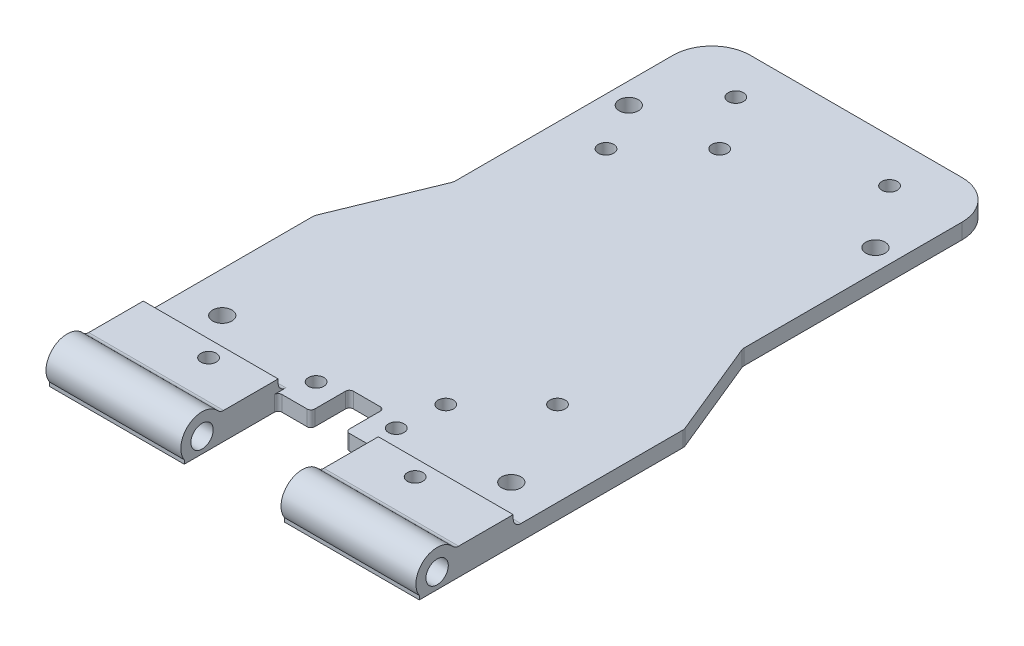
SolidWorks part; units mm, degrees
ref_plane "Front Plane" through (0, 0, 0) normal (0, 0, 1) x (1, 0, 0)
ref_plane "Top Plane" through (0, 0, 0) normal (0, 1, 0) x (1, 0, 0)
ref_plane "Right Plane" through (0, 0, 0) normal (1, 0, 0) x (0, 0, -1)
sketch "Sketch1" plane through (0, 0, 0) normal (0, 1, 0) x (1, 0, 0)
  line L0 (0, 0) -> (0, 23)
  line L1 (0, 23) -> (8.5, 23)
  line L2 (26, 23) -> (26, 0)
  line L3 (26, 0) -> (61, 0)
  line L4 (61, 0) -> (61, 28.8014)
  line L5 (61, 28.8014) -> (50.5, 57.5081) construction
  line L6 (50.5, 93.0296) -> (50.5, 160)
  line L7 (50.5, 160) -> (-24.5, 160)
  line L8 (-24.5, 160) -> (-24.5, 93.0296)
  line L9 (-24.5, 57.5081) -> (-35, 28.8014) construction
  line L10 (-35, 28.8014) -> (-35, 0)
  line L11 (-35, 0) -> (0, 0)
  line L12 (17.5, 23) -> (26, 23)
  line L14 (8.5, 23) -> (8.5, 33)
  line L15 (8.5, 33) -> (17.5, 33)
  line L16 (17.5, 23) -> (17.5, 33)
  line L17 (-35, 28.8014) -> (-35, 67.4062)
  line L24 (-35, 67.4062) -> (-24.5, 93.0296)
  line L26 (61, 67.4062) -> (50.5, 93.0296)
  line L27 (61, 28.8014) -> (61, 67.4062)
  point P16 (13, 33)
  point P22 (13, 160)
  point P24 (12, 23)
  dimension "D1" = 26
  dimension "D2" = 23
  dimension "D3" = 75
  dimension "D4" = 96
  dimension "D5" = 38.6048
  dimension "D6" = 28.8014
  dimension "D7" = 9
  dimension "D8" = 10
  dimension "D11" = 160
  dimension "D12" = 25.6234
extrude "Boss-Extrude1" add sketch "Sketch1" along normal blind 3
sketch "Sketch5" plane through (0, 3, 0) normal (0, 1, 0) x (1, 0, 0)
  line L0 (26, 23) -> (26, 0) construction
  line L1 (0, 23) -> (-35, 23)
  line L2 (0, 23) -> (0, 0)
  line L3 (0, 0) -> (-35, 0)
  line L4 (-35, 23) -> (-35, 0)
  line L5 (26, 23) -> (61, 23)
  line L6 (26, 23) -> (26, 0)
  line L7 (26, 0) -> (61, 0)
  line L8 (61, 23) -> (61, 0)
extrude "Boss-Extrude2" add sketch "Sketch5" along normal blind 3
sketch "Sketch6" plane through (-35, 0, 0) normal (-1, 0, 0) x (0, 0, 1)
  line L0 (0, 6) -> (0, 0) construction
  line L1 (0, 6) -> (-3.2478, 6)
  line L2 (-3.2478, 0) -> (0, 0)
  line L3 (0, 6) -> (0, 0)
  arc A0 (-3.2478, 0) -> (-3.2478, 6) centre (-3.2478, 3) ccw
  dimension "D1" = 6
sketch "Sketch11" plane through (-35, 0, 0) normal (-1, 0, 0) x (0, 0, 1)
  line L0 (0, 6) -> (0, 0) construction
  circle A0 centre (-3.2478, 3) radius 2.9
  dimension "D1" = 5.8
  dimension "D2" = 3.2478
sketch "Sketch12" plane through (-35, 0, 0) normal (-1, 0, 0) x (0, 0, 1)
  line L0 (-7.8576, 0) -> (1.3619, 0)
  line L1 (-67.4062, 0) -> (0, 0) construction
  arc A0 (1.3619, 0) -> (-7.8576, 0) centre (-3.2478, 3) ccw
  dimension "D1" = 11
extrude "Boss-Extrude5" add sketch "Sketch12" against normal up to surface (35 mm away) up to face at (0, 3, -13.8)
sketch "Sketch15" plane through (61, 0, 0) normal (1, 0, 0) x (0, 0, -1)
  line L0 (7.8576, 0) -> (-1.3619, 0)
  arc A0 (7.8576, 0) -> (-1.3619, 0) centre (3.2478, 3) ccw
extrude "Boss-Extrude8" add sketch "Sketch15" against normal up to surface (35 mm away) up to face at (26, 3, -13.8)
sketch "Sketch16" plane through (61, 0, 0) normal (1, 0, 0) x (0, 0, -1)
  circle A0 centre (3.2478, 3) radius 2.85
  dimension "D1" = 5.7
extrude "Cut-Extrude1" cut sketch "Sketch11" against normal up to surface (96 mm away)
sketch "Sketch14" plane through (0, 0, 0) normal (0, -1, 0) x (1, 0, 0)
  line L16 (50.5, -93.0296) -> (61, -67.4062)
  line L17 (61, -67.4062) -> (61, 1.3619)
  line L18 (61, 1.3619) -> (26, 1.3619)
  line L19 (26, 1.3619) -> (26, -23)
  line L20 (26, -23) -> (17.5, -23)
  line L21 (17.5, -23) -> (17.5, -33)
  line L22 (17.5, -33) -> (8.5, -33)
  line L23 (8.5, -33) -> (8.5, -23)
  line L24 (8.5, -23) -> (0, -23)
  line L25 (0, -23) -> (0, 1.3619)
  line L26 (0, 1.3619) -> (-35, 1.3619)
  line L27 (-35, 1.3619) -> (-35, -67.4062)
  line L28 (50.5, -93.0296) -> (61, -67.4062)
  line L29 (-24.5, -93.0296) -> (-24.5, -160)
  line L30 (-24.5, -160) -> (50.5, -160)
  line L31 (50.5, -160) -> (50.5, -93.0296)
  line L33 (61, -67.4062) -> (61, 1.3619)
  line L35 (26, 1.3619) -> (26, -23)
  line L36 (26, -23) -> (17.5, -23)
  line L37 (17.5, -23) -> (17.5, -33)
  line L38 (17.5, -33) -> (8.5, -33)
  line L39 (8.5, -33) -> (8.5, -23)
  line L40 (8.5, -23) -> (0, -23)
  line L41 (0, -23) -> (0, 1.3619)
  line L42 (0, 1.3619) -> (-35, 1.3619)
  line L43 (-35, 1.3619) -> (-35, -67.4062)
  line L45 (-24.5, -93.0296) -> (-24.5, -160)
  line L46 (-24.5, -160) -> (50.5, -160)
  line L47 (50.5, -160) -> (50.5, -93.0296)
  line L48 (61, 1.3619) -> (26, 1.3619)
  line L49 (-35, -67.4062) -> (-24.5, -93.0296)
  line L50 (-35, -67.4062) -> (-24.5, -93.0296)
  dimension "D1" = 0
extrude "Boss-Extrude7" add sketch "Sketch14" along normal blind 1
sketch "Sketch17" plane through (0, 3, 0) normal (0, 1, 0) x (1, 0, 0)
  circle A0 centre (-24.5, 33) radius 2.5
  circle A1 centre (50.5, 33) radius 2.5
  dimension "D1" = 5
extrude "Cut-Extrude2" cut sketch "Sketch17" against normal blind 10
sketch "Sketch18" plane through (0, 3, 0) normal (0, 1, 0) x (1, 0, 0)
  line L0 (13, 160) -> (13, -20.8906) construction
  line L1 (50.5, 160) -> (-24.5, 160) construction
  line L2 (-24.5, 160) -> (-24.5, 93.0296) construction
  circle A0 centre (-6.9417, 148.7167) radius 2
  circle A1 centre (32.9417, 148.7167) radius 2
  dimension "D2" = 4
  dimension "D1" = 17.5583
  dimension "D3" = 11.2833
extrude "Cut-Extrude3" cut sketch "Sketch18" against normal blind 10
sketch "Sketch19" plane through (0, 3, 0) normal (0, 1, 0) x (1, 0, 0)
  line L0 (-24.5, 160) -> (-24.5, 93.0296) construction
  line L1 (-15.1744, 138) -> (5.8256, 138) construction
  line L2 (-15.1744, 138) -> (-15.1744, 117) construction
  line L3 (-15.1744, 117) -> (5.8256, 117) construction
  line L4 (5.8256, 138) -> (5.8256, 117) construction
  line L5 (20.9999, 60) -> (41.9999, 60) construction
  line L6 (20.9999, 60) -> (20.9999, 39) construction
  line L7 (20.9999, 39) -> (41.9999, 39) construction
  line L8 (41.9999, 60) -> (41.9999, 39) construction
  line L9 (50.5, 160) -> (-24.5, 160) construction
  line L10 (-15.1744, 138) -> (5.8256, 117) construction
  line L11 (20.9999, 60) -> (41.9999, 39) construction
  circle A0 centre (-12.1744, 120.25) radius 2
  circle A1 centre (2.5756, 135) radius 2
  circle A2 centre (24.4999, 42) radius 2
  circle A3 centre (38.9999, 56.5) radius 2
  dimension "D7" = 4
  dimension "D11" = 4
  dimension "D1" = 21
  dimension "D2" = 9.3256
  dimension "D3" = 22
  dimension "D4" = 57
  dimension "D5" = 15.1743
  dimension "D6" = 3.25
  dimension "D8" = 3
  dimension "D9" = 3.5
  dimension "D10" = 3
extrude "Cut-Extrude4" cut sketch "Sketch19" against normal up to surface (4 mm away) up to face at (-6.9417, -1, -150.7167)
sketch "Sketch21" plane through (0, 6, 0) normal (0, 1, 0) x (1, 0, 0)
  line L0 (-35, 23) -> (-35, 7.8576) construction
  line L2 (13, 50.031) -> (13, -12.0537) construction
  line L3 (0, 23) -> (-35, 23) construction
  line L4 (-35, 67.4062) -> (-35, 23) construction
  line L5 (0, 23) -> (8.5, 23) construction
  circle A0 centre (-13.8, 18.7451) radius 2
  circle A1 centre (2.6, 30.245) radius 2
  circle A4 centre (23.4, 30.245) radius 2
  circle A5 centre (39.8, 18.7451) radius 2
  dimension "D1" = 4
  dimension "D2" = 21.2
  dimension "D3" = 4.2549
  dimension "D6" = 4
  dimension "D4" = 37.6
  dimension "D5" = 7.245
extrude "Cut-Extrude5" cut sketch "Sketch21" against normal up to surface (7 mm away) up to face at (-12.1744, -1, -122.25)
sketch "Sketch22" plane through (0, 3, 0) normal (0, 1, 0) x (1, 0, 0)
  line L0 (13, 160) -> (13, 23.9246) construction
  line L1 (50.5, 160) -> (-24.5, 160) construction
  line L2 (-24.5, 160) -> (-24.5, 93.0296) construction
  circle A0 centre (-19, 133) radius 2.5
  circle A1 centre (45, 133) radius 2.5
  dimension "D1" = 5
  dimension "D4" = 5
  dimension "D2" = 5.5
  dimension "D3" = 27
extrude "Cut-Extrude6" cut sketch "Sketch22" against normal up to surface (4 mm away) up to face at (-13.8, -1, -20.7451)
fillet "Fillet1" radius 10 2 edges at (-24.5, 1, -160) (50.5, 1, -160)
fillet "Fillet2" radius 2 6 edges at (50.5, 1, -93.0296) (61, 1, -67.4062) (-17.5, 6, -7.8576) (43.5, 6, -7.8576) (-17.5, 3, -23) (43.5, 3, -23)
fillet "Fillet3" radius 2 2 edges at (-24.5, 1, -93.0296) (-35, 1, -67.4062)
fillet "Fillet4" radius 1 6 edges at (26, 1, -23) (17.5, 1, -23) (17.5, 1, -33) (8.5, 1, -33) (8.5, 1, -23) (0, 1, -23)
